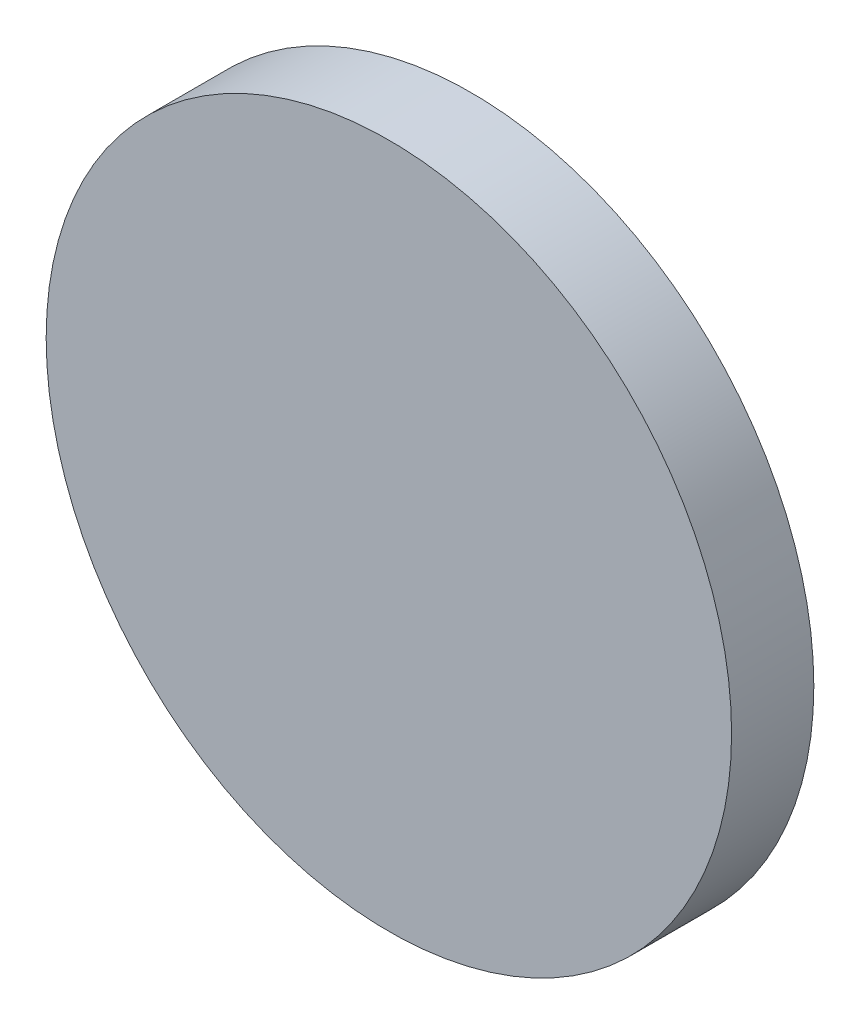
SolidWorks part; units mm, degrees
ref_plane "Front Plane" through (0, 0, 0) normal (0, 0, 1) x (1, 0, 0)
ref_plane "Top Plane" through (0, 0, 0) normal (0, 1, 0) x (1, 0, 0)
ref_plane "Right Plane" through (0, 0, 0) normal (1, 0, 0) x (0, 0, -1)
sketch "Sketch1" plane through (0, 0, 0) normal (0, 0, 1) x (1, 0, 0)
  circle A0 centre (0, 0) radius 6.25
  dimension "D1" = 12.5
extrude "Boss-Extrude1" add sketch "Sketch1" along normal blind 1.5
